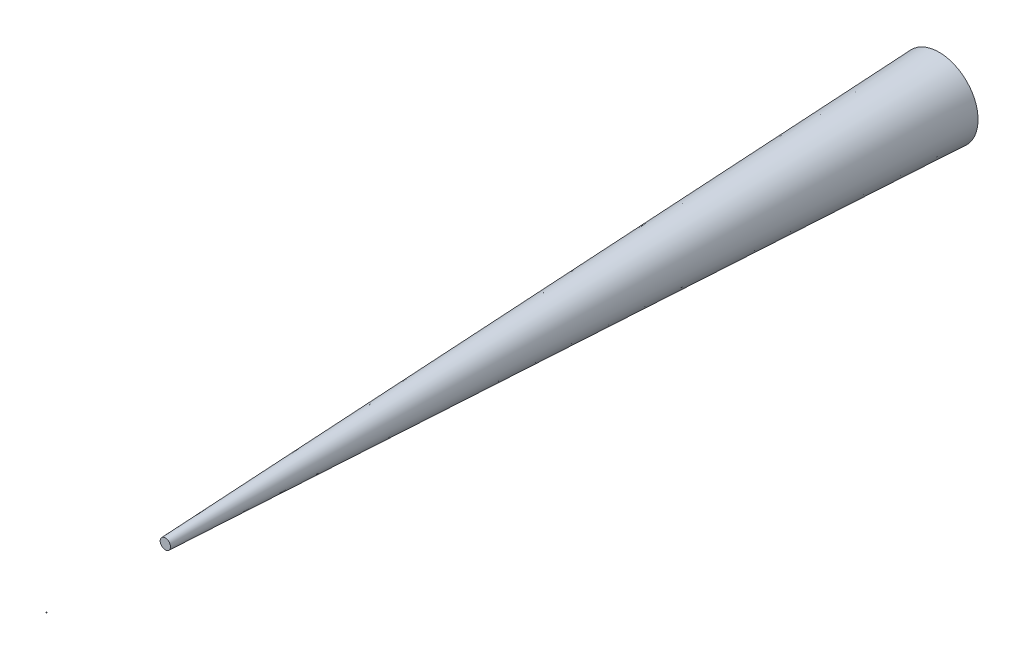
SolidWorks part; units mm, degrees
ref_plane "Front Plane" through (0, 0, 0) normal (0, 0, 1) x (1, 0, 0)
ref_plane "Top Plane" through (0, 0, 0) normal (0, 1, 0) x (1, 0, 0)
ref_plane "Right Plane" through (0, 0, 0) normal (1, 0, 0) x (0, 0, -1)
sketch "Sketch1" plane through (0, 0, 0) normal (0, 1, 0) x (1, 0, 0)
  line L0 (0, 0) -> (0, 1500)
  line L1 (0, 1500) -> (65.4914, 1500)
  line L2 (65.4914, 1500) -> (0, 0)
  dimension "D1" = 2.5
  dimension "D2" = 1500
revolve "Revolve1" add sketch "Sketch1" angle 360 about L0
sketch "Sketch2" plane through (0, 0, 0) normal (1, 0, 0) x (0, 0, -1)
  line L0 (0, 0) -> (200, -8.7322)
  line L1 (0, 0) -> (1500, -65.4914) construction
  line L2 (200, -8.7322) -> (200, 8.7322)
  line L3 (1500, 65.4914) -> (0, 0) construction
  line L4 (200, 8.7322) -> (0, 0)
  dimension "D1" = 200
extrude "Cut-Extrude1" cut sketch "Sketch2" against normal through all both and the other way through all
sketch "Sketch4" plane through (0, 0, 0) normal (0, 0, 1) x (1, 0, 0)
  line L1 (-0.5, 0.5) -> (0.5, 0.5)
  line L2 (-0.5, 0.5) -> (-0.5, -0.5)
  line L3 (-0.5, -0.5) -> (0.5, -0.5)
  line L4 (0.5, 0.5) -> (0.5, -0.5)
  line L5 (-0.5, 0.5) -> (0.5, -0.5) construction
  line L6 (-0.5, -0.5) -> (0.5, 0.5) construction
  point P0 (0, 0)
  dimension "D1" = 1
extrude "Boss-Extrude1" add sketch "Sketch4" against normal blind 1 separate body
